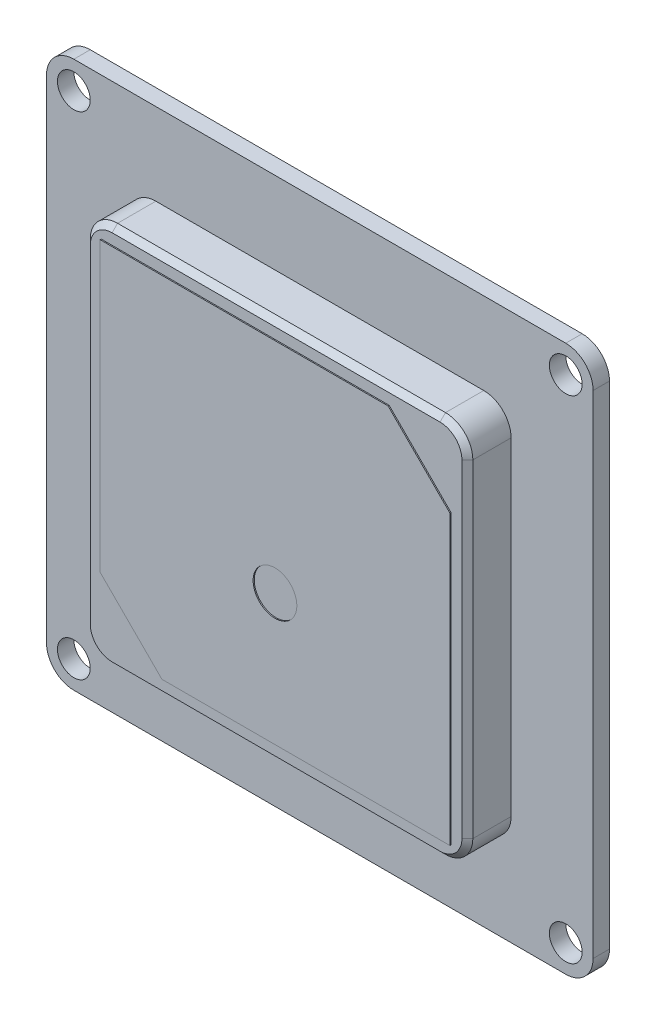
SolidWorks part; units mm, degrees
ref_plane "Ebene vorne" through (0, 0, 0) normal (0, 0, 1) x (1, 0, 0)
ref_plane "Ebene oben" through (0, 0, 0) normal (0, 1, 0) x (1, 0, 0)
ref_plane "Ebene rechts" through (0, 0, 0) normal (1, 0, 0) x (0, 0, -1)
ref_plane "Plane1" through (0, 0, 1.5) normal (0, 0, 1) x (1, 0, 0)
sketch "Sketch1" plane through (0, 0, 1.5) normal (0, 0, 1) x (1, 0, 0)
  line L0 (25, 25) -> (-25, 25)
  line L1 (-25, 25) -> (-25, -25)
  line L2 (-25, -25) -> (25, -25)
  line L3 (25, -25) -> (25, 25)
extrude "Boss-Extrude1" add sketch "Sketch1" against normal blind 1.5
sketch "Sketch2" plane through (0, 0, 1.5) normal (0, 0, 1) x (1, 0, 0)
  line L0 (-17.5, 17.5) -> (17.5, 17.5)
  line L1 (17.5, 17.5) -> (17.5, -17.5)
  line L2 (17.5, -17.5) -> (-17.5, -17.5)
  line L3 (-17.5, -17.5) -> (-17.5, 17.5)
extrude "Boss-Extrude2" add sketch "Sketch2" along normal blind 4
sketch "Sketch3" plane through (0, 0, 5.5) normal (0, 0, 1) x (1, 0, 0)
  line L0 (16, -16) -> (-16, -16)
  line L1 (-16, -16) -> (-16, 16)
  line L2 (-16, 16) -> (16, 16)
  line L3 (16, 16) -> (16, -16)
extrude "Boss-Extrude3" add sketch "Sketch3" along normal blind 0.1
hole_wizard "Ø3.0 (3) Diameter Hole1" positions "Sketch5" profile "Sketch4" hole size "Ø3.0" standard "ANSI Metric"
sketch "Sketch5" plane through (0, 0, 1.5) normal (0, 0, 1) x (1, 0, 0)
  point P0 (22.5, -22.5)
  point P1 (-22.5, 22.5)
  point P2 (22.5, 22.5)
  point P3 (-22.5, -22.5)
sketch "Sketch4" plane through (22.5, -22.5, 1.5) normal (1, 0, 0) x (0, -1, 0)
  line L0 (0, 0) -> (0, 1.5)
  line L1 (0, 1.5) -> (1.5, 1.5)
  line L2 (1.5, 1.5) -> (1.5, 0)
  line L5 (1.5, 0) -> (0, 0)
  line L11 (0, -6.35) -> (0, 107.95) construction
  dimension "Thru Hole Dia." = 3
  dimension "Thru Hole Depth" = 1.5
hole_wizard "Ø4.0 (4) Diameter Hole1" positions "Sketch7" profile "Sketch6" hole size "Ø4.0" standard "ANSI Metric"
sketch "Sketch7" plane through (0, 0, 5.6) normal (0, 0, 1) x (1, 0, 0)
  point P0 (0, -4)
sketch "Sketch6" plane through (0, -4, 5.6) normal (1, 0, 0) x (0, -1, 0)
  line L0 (0, 0) -> (0, 0.1)
  line L1 (0, 0.1) -> (2, 0.1)
  line L2 (2, 0.1) -> (2, 0)
  line L5 (2, 0) -> (0, 0)
  line L10 (0, 0.1) -> (-2, 0.1) construction
  line L11 (0, -6.35) -> (0, 107.95) construction
  dimension "Hole Dia." = 4
  dimension "Hole Depth" = 0.1
  dimension "Drill Angle" = 180
fillet "Fillet1" radius 2.5 8 edges at (25, -25, 0.75) (25, 25, 0.75) (-25, -25, 0.75) (-25, 25, 0.75) (17.5, -17.5, 3.5) (17.5, 17.5, 3.5) (-17.5, -17.5, 3.5) (-17.5, 17.5, 3.5)
chamfer "Chamfer1" distance 5.6569 angle 45 2 edges at (-16, -16, 5.55) (16, 16, 5.55)
chamfer "Chamfer2" distance 0.5 angle 45 8 edges at (17.5, 0, 5.5) (16.7678, -16.7678, 5.5) (16.7678, 16.7678, 5.5) (0, -17.5, 5.5) (0, 17.5, 5.5) (-16.7678, -16.7678, 5.5) (-16.7678, 16.7678, 5.5) (-17.5, 0, 5.5)
sketch "Sketch8" plane through (0, 0, 0) normal (0, 0, -1) x (-1, 0, 0)
  line L0 (25, 22.5) -> (25, -22.5) construction
  line L1 (-5, 15.6181) -> (25, 15.6181)
  line L2 (-5, 15.6181) -> (-5, -14.3819)
  line L3 (-5, -14.3819) -> (25, -14.3819)
  line L4 (25, 15.6181) -> (25, -14.3819)
  dimension "D1" = 30
  dimension "D2" = 30
extrude "Boss-Extrude4" add sketch "Sketch8" along normal blind 5
